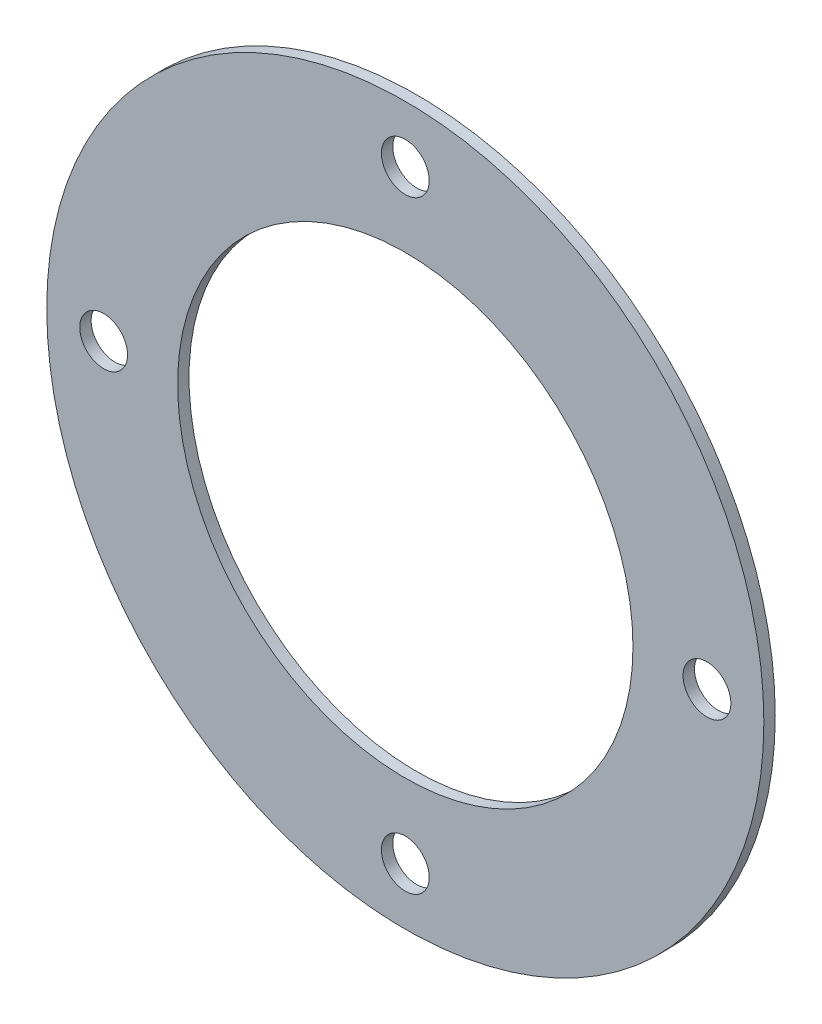
SolidWorks part; units mm, degrees
material "Thornel Mat VMA"
ref_plane "前视基准面" through (0, 0, 0) normal (0, 0, 1) x (1, 0, 0)
ref_plane "上视基准面" through (0, 0, 0) normal (0, 1, 0) x (1, 0, 0)
ref_plane "右视基准面" through (0, 0, 0) normal (1, 0, 0) x (0, 0, -1)
other "Configuration Table"
sketch "草图1" plane through (0, 0, 0) normal (0, 0, 1) x (1, 0, 0)
  circle A0 centre (0, 0) radius 31.5
  circle A1 centre (0, 0) radius 20
  circle A2 centre (0, 0) radius 26.5 construction
  circle A3 centre (0, 26.5) radius 2.1
  circle A4 centre (26.5, 0) radius 2.1
  circle A5 centre (0, -26.5) radius 2.1
  circle A6 centre (-26.5, 0) radius 2.1
  point P16 (0, 0)
  dimension "D1" = 40
  dimension "D2" = 63
  dimension "D3" = 53
  dimension "D4" = 4.2
  dimension "D5" = 4
extrude "凸台-拉伸1" add sketch "草图1" along normal blind 1
